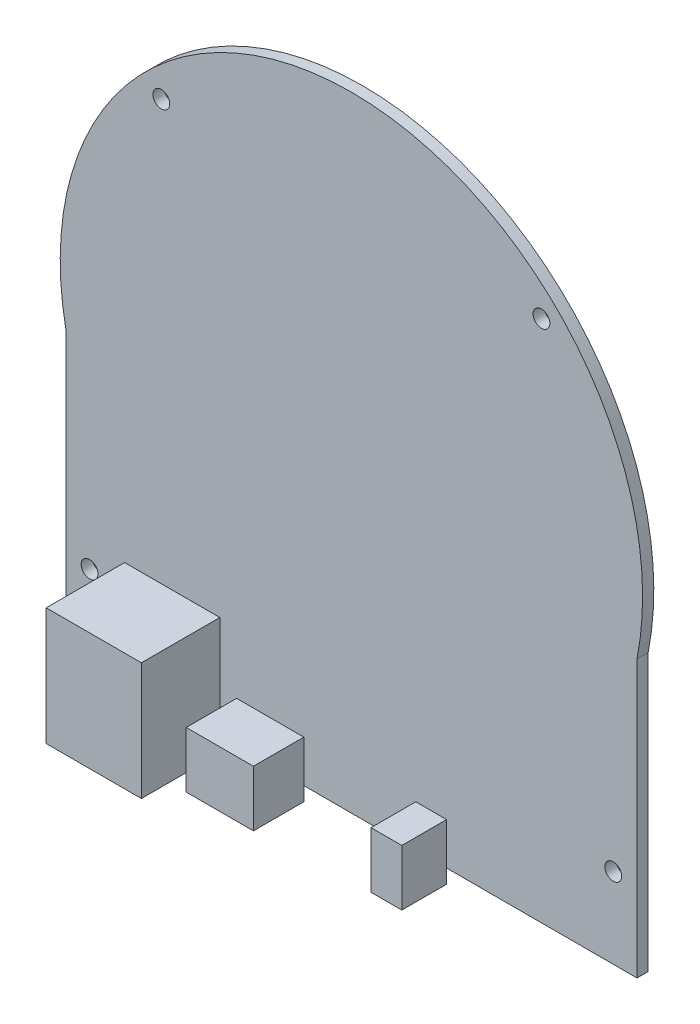
SolidWorks part; units mm, degrees
ref_plane "Plan de face" through (0, 0, 0) normal (0, 0, 1) x (1, 0, 0)
ref_plane "Plan de dessus" through (0, 0, 0) normal (0, 1, 0) x (1, 0, 0)
ref_plane "Plan de droite" through (0, 0, 0) normal (1, 0, 0) x (0, 0, -1)
sketch "Esquisse1" plane through (0, 0, 0) normal (0, 0, 1) x (1, 0, 0)
  line L0 (-51, -59.5) -> (51, -59.5)
  line L1 (-51, -59.5) -> (-51, -10.1489)
  line L2 (51, -59.5) -> (51, -10.1489)
  line L3 (0, 0) -> (-92.6782, 92.6782) construction
  line L4 (0, 0) -> (-109.0276, -105.2868) construction
  line L5 (0, 0) -> (0, 109.9392) construction
  arc A0 (51, -10.1489) -> (-51, -10.1489) centre (0, 0) ccw
  circle A1 centre (0, 0) radius 48 construction
  circle A2 centre (0, 0) radius 65 construction
  circle A3 centre (-33.9411, 33.9411) radius 1.5
  circle A4 centre (-46.7571, -45.1528) radius 1.5
  circle A5 centre (33.9411, 33.9411) radius 1.5
  circle A6 centre (46.7571, -45.1528) radius 1.5
  dimension "D1" = 104
  dimension "D5" = 96
  dimension "D6" = 130
  dimension "D9" = 3
  dimension "D10" = 3
  dimension "D2" = 59.5
  dimension "D3" = 51
  dimension "D4" = 102
  dimension "D7" = 45
  dimension "D8" = 46
extrude "Boss.-Extru.1" add sketch "Esquisse1" along normal blind 2
ref_plane "Plan1" through (0, -61.5, 0) normal (0, -1, 0) x (1, 0, 0)
sketch "Esquisse2" plane through (0, -61.5, 0) normal (0, -1, 0) x (1, 0, 0)
  line L0 (-31.5, 16.5) -> (-31.5, 2.5) construction
  line L1 (-40, 16.5) -> (-23, 16.5)
  line L2 (-40, 16.5) -> (-40, 2.5)
  line L3 (-40, 2.5) -> (-23, 2.5)
  line L4 (-23, 16.5) -> (-23, 2.5)
  line L5 (-29.5, 3.5) -> (-33.5, 3.5)
  line L6 (-33.5, 3.5) -> (-33.5, 4.5)
  line L7 (-33.5, 4.5) -> (-34.5, 4.5)
  line L8 (-34.5, 4.5) -> (-34.5, 6)
  line L9 (-34.5, 6) -> (-39, 6)
  line L10 (-39, 6) -> (-39, 14.5)
  line L11 (-39, 14.5) -> (-24, 14.5)
  line L12 (-29.5, 3.5) -> (-29.5, 4.5)
  line L13 (-29.5, 4.5) -> (-28.5, 4.5)
  line L14 (-28.5, 4.5) -> (-28.5, 6)
  line L15 (-28.5, 6) -> (-24, 6)
  line L16 (-24, 6) -> (-24, 14.5)
  point P16 (-31.5, 3.5)
  point P21 (-31.5, 14.5)
  dimension "D1" = 17
  dimension "D2" = 14
  dimension "D3" = 2.5
  dimension "D4" = 40
  dimension "D5" = 2
  dimension "D6" = 1
  dimension "D7" = 1
  dimension "D8" = 1.5
  dimension "D9" = 2
  dimension "D10" = 1
  dimension "D11" = 1
extrude "Boss.-Extru.2" add sketch "Esquisse2" against normal blind 21 separate body contours L2 L3 L4 L1
sketch "Esquisse3" plane through (0, -61.5, 0) normal (0, -1, 0) x (1, 0, 0)
  line L11 (-39, 14.5) -> (-24, 14.5) construction
  line L12 (-39, 6) -> (-39, 14.5) construction
  line L13 (-34.5, 6) -> (-39, 6) construction
  line L14 (-34.5, 4.5) -> (-34.5, 6) construction
  line L15 (-33.5, 4.5) -> (-34.5, 4.5) construction
  line L16 (-33.5, 3.5) -> (-33.5, 4.5) construction
  line L17 (-29.5, 3.5) -> (-33.5, 3.5) construction
  line L18 (-29.5, 3.5) -> (-29.5, 4.5) construction
  line L19 (-29.5, 4.5) -> (-28.5, 4.5) construction
  line L20 (-28.5, 4.5) -> (-28.5, 6) construction
  line L21 (-28.5, 6) -> (-24, 6) construction
  line L22 (-24, 6) -> (-24, 14.5) construction
  line L23 (-39, 14.5) -> (-24, 14.5)
  line L24 (-39, 6) -> (-39, 14.5)
  line L25 (-34.5, 6) -> (-39, 6)
  line L26 (-34.5, 4.5) -> (-34.5, 6)
  line L27 (-33.5, 4.5) -> (-34.5, 4.5)
  line L28 (-33.5, 3.5) -> (-33.5, 4.5)
  line L29 (-29.5, 3.5) -> (-33.5, 3.5)
  line L30 (-29.5, 3.5) -> (-29.5, 4.5)
  line L31 (-29.5, 4.5) -> (-28.5, 4.5)
  line L32 (-28.5, 4.5) -> (-28.5, 6)
  line L33 (-28.5, 6) -> (-24, 6)
  line L34 (-24, 6) -> (-24, 14.5)
extrude "Enlèv. mat.-Extru.1" cut sketch "Esquisse3" against normal blind 15
sketch "Esquisse4" plane through (0, -61.5, 0) normal (0, -1, 0) x (1, 0, 0)
  line L0 (-23, 16.5) -> (-23, 2.5) construction
  line L1 (-20, 2.5) -> (-8, 2.5)
  line L2 (-20, 2.5) -> (-20, 11.5)
  line L3 (-20, 11.5) -> (-8, 11.5)
  line L4 (-8, 2.5) -> (-8, 11.5)
  dimension "D1" = 3
  dimension "D2" = 12
  dimension "D3" = 9
  dimension "D4" = 2.5
extrude "Boss.-Extru.3" add sketch "Esquisse4" against normal blind 10 separate body
sketch "Esquisse5" plane through (0, -61.5, 0) normal (0, -1, 0) x (1, 0, 0)
  line L0 (-19.5, 3) -> (-8.5, 3)
  line L1 (-8.5, 3) -> (-8.5, 10)
  line L2 (-8.5, 10) -> (-9, 10)
  line L3 (-9, 10) -> (-9, 10.25)
  line L4 (-9, 10.25) -> (-8.5, 10.25)
  line L5 (-8.5, 10.25) -> (-8.5, 11)
  line L6 (-8.5, 11) -> (-10.5, 11)
  line L7 (-10.5, 11) -> (-10.5, 10.25)
  line L8 (-10.5, 10.25) -> (-10, 10.25)
  line L9 (-10, 10.25) -> (-10, 10)
  line L10 (-10, 10) -> (-10.75, 10)
  line L11 (-8, 2.5) -> (-8, 11.5) construction
  line L12 (-20, 2.5) -> (-8, 2.5) construction
  line L13 (-12.25, 10) -> (-13, 10)
  line L14 (-12.25, 10.25) -> (-12.25, 10)
  line L15 (-12.75, 10.25) -> (-12.25, 10.25)
  line L16 (-12.75, 11) -> (-12.75, 10.25)
  line L17 (-10.75, 11) -> (-12.75, 11)
  line L18 (-10.75, 10.25) -> (-10.75, 11)
  line L19 (-11.25, 10.25) -> (-10.75, 10.25)
  line L20 (-11.25, 10) -> (-11.25, 10.25)
  line L21 (-10.75, 10) -> (-11.25, 10)
  line L22 (-14.5, 10) -> (-15.25, 10)
  line L23 (-14.5, 10.25) -> (-14.5, 10)
  line L24 (-15, 10.25) -> (-14.5, 10.25)
  line L25 (-15, 11) -> (-15, 10.25)
  line L26 (-13, 11) -> (-15, 11)
  line L27 (-13, 10.25) -> (-13, 11)
  line L28 (-13.5, 10.25) -> (-13, 10.25)
  line L29 (-13.5, 10) -> (-13.5, 10.25)
  line L30 (-13, 10) -> (-13.5, 10)
  line L31 (-16.75, 10) -> (-17.5, 10)
  line L32 (-16.75, 10.25) -> (-16.75, 10)
  line L33 (-17.25, 10.25) -> (-16.75, 10.25)
  line L34 (-17.25, 11) -> (-17.25, 10.25)
  line L35 (-15.25, 11) -> (-17.25, 11)
  line L36 (-15.25, 10.25) -> (-15.25, 11)
  line L37 (-15.75, 10.25) -> (-15.25, 10.25)
  line L38 (-15.75, 10) -> (-15.75, 10.25)
  line L39 (-15.25, 10) -> (-15.75, 10)
  line L40 (-19, 10) -> (-19.5, 10)
  line L41 (-19, 10.25) -> (-19, 10)
  line L42 (-19.5, 10.25) -> (-19, 10.25)
  line L43 (-19.5, 11) -> (-19.5, 10.25)
  line L44 (-17.5, 11) -> (-19.5, 11)
  line L45 (-17.5, 10.25) -> (-17.5, 11)
  line L46 (-18, 10.25) -> (-17.5, 10.25)
  line L47 (-18, 10) -> (-18, 10.25)
  line L48 (-17.5, 10) -> (-18, 10)
  line L50 (-19.5, 10) -> (-19.5, 3)
  dimension "D1" = 2
  dimension "D2" = 0.5
  dimension "D3" = 0.5
  dimension "D4" = 0.75
  dimension "D5" = 0.75
  dimension "D6" = 0.5
  dimension "D7" = 0.5
  dimension "D8" = 0.25
  dimension "D9" = 7
  dimension "D10" = 0.75
  dimension "D11" = 5
extrude "Enlèv. mat.-Extru.2" cut sketch "Esquisse5" against normal blind 8
sketch "Esquisse6" plane through (0, -53.5, 0) normal (0, -1, 0) x (1, 0, 0)
  circle A0 centre (-18.5478, 6.6182) radius 0.375
  circle A1 centre (-16.2978, 6.6182) radius 0.375
  circle A2 centre (-14.0478, 6.6182) radius 0.375
  circle A3 centre (-11.7978, 6.6182) radius 0.375
  circle A4 centre (-9.5478, 6.6182) radius 0.375
  dimension "D1" = 0.75
  dimension "D2" = 5
extrude "Boss.-Extru.4" add sketch "Esquisse6" along normal blind 6
sketch "Esquisse7" plane through (0, -61.5, 0) normal (0, -1, 0) x (1, 0, 0)
  line L1 (12, 2.5) -> (17.5, 2.5)
  line L2 (12, 2.5) -> (12, 10.5)
  line L3 (12, 10.5) -> (17.5, 10.5)
  line L4 (17.5, 2.5) -> (17.5, 10.5)
  dimension "D1" = 5.5
  dimension "D2" = 8
  dimension "D3" = 2.5
  dimension "D4" = 20
extrude "Boss.-Extru.5" add sketch "Esquisse7" against normal blind 10 separate body
sketch "Esquisse8" plane through (0, -61.5, 0) normal (0, -1, 0) x (1, 0, 0)
  line L0 (14.75, 10.5) -> (14.75, -2.8248) construction
  line L1 (17.5, 10.5) -> (12, 10.5) construction
  circle A0 centre (14.75, 6.9772) radius 2
  dimension "D1" = 4
extrude "Enlèv. mat.-Extru.3" cut sketch "Esquisse8" against normal blind 8
sketch "Esquisse9" plane through (0, -53.5, 0) normal (0, -1, 0) x (1, 0, 0)
  circle A0 centre (14.75, 6.9772) radius 0.5
  dimension "D1" = 1
extrude "Boss.-Extru.6" add sketch "Esquisse9" along normal blind 8
sketch "Esquisse10" plane through (0, 0, 2) normal (0, 0, 1) x (1, 0, 0)
  line L1 (0, 0) -> (-24, 0)
  line L2 (0, 0) -> (0, 24)
  line L3 (0, 24) -> (-24, 24)
  line L4 (-24, 0) -> (-24, 24)
  line L5 (12, 17) -> (24, 17)
  line L6 (12, 17) -> (12, -7)
  line L7 (12, -7) -> (24, -7)
  line L8 (24, 17) -> (24, -7)
  line L9 (30, 17) -> (42, 17)
  line L10 (30, 17) -> (30, -7)
  line L11 (30, -7) -> (42, -7)
  line L12 (42, 17) -> (42, -7)
  line L13 (-30, -30) -> (-15, -30)
  line L14 (-30, -30) -> (-30, -10)
  line L15 (-30, -10) -> (-15, -10)
  line L16 (-15, -30) -> (-15, -10)
  dimension "D1" = 24
  dimension "D2" = 24
  dimension "D3" = 24
  dimension "D4" = 24
  dimension "D5" = 12
  dimension "D6" = 12
  dimension "D7" = 17
  dimension "D8" = 12
  dimension "D9" = 6
  dimension "D10" = 15
  dimension "D11" = 20
  dimension "D12" = 10
  dimension "D13" = 15
extrude "Boss.-Extru.7" [suppressed] add sketch "Esquisse10" along normal blind 3
sketch "Esquisse11" plane through (0, 0, 2) normal (0, 0, 1) x (1, 0, 0)
  circle A0 centre (23.8359, -44.6172) radius 2.8691
  circle A1 centre (15.8203, -39.5547) radius 3.1641
  circle A2 centre (8.2266, -39.5547) radius 2.4051
  circle A3 centre (14.1328, -32.1719) radius 2.54
  circle A4 centre (5.8215, -32.1719) radius 3.3929
  circle A5 centre (5.8215, -22.0469) radius 2.8221
  circle A6 centre (14.1328, -19.2247) radius 3.5262
  circle A7 centre (-1.2656, -35.5647) radius 1.7773
extrude "Boss.-Extru.8" [suppressed] add sketch "Esquisse11" along normal blind 8
ref_plane "Plan2" [suppressed] through (-23.75, 0, 0) normal (-1, 0, 0) x (0, 0, 1)
sketch "Esquisse12" [suppressed] plane through (-23.75, 0, 0) normal (-1, 0, 0) x (0, 0, 1)
  line L0 (3.5, 0) -> (3.5, -1) construction
  line L1 (5, 0) -> (2, 0) construction
  line L2 (3.5, -1) -> (2, -1) construction
  line L3 (2, 17) -> (2, -7) construction
  spline S0 degree 3 poles (3.5, 0) (3.5, -0.25) (3.5, -0.5) (3.5, -0.75) (3.5, -0.8001) (3.5, -0.9002) (3.2752, -1) (3.1751, -1) (3.125, -1) (2.75, -1) (2.375, -1) (2, -1) knots 0 0 0 0 0.322484 0.322484 0.322484 0.387081 0.451677 0.516273 0.516273 0.516273 1 1 1 1
  dimension "D1" = 1
sketch "Esquisse13" [suppressed] plane through (0, 0, 0) normal (0, -1, 0) x (1, 0, 0)
  circle A0 centre (-23.75, 3.5) radius 0.15
  dimension "D1" = 0.3
sweep "Balayage1" [suppressed] add profiles "Esquisse13" path "Esquisse12"
pattern_linear "Répétition linéaire2" [suppressed] count 48 spacing 0.5
ref_plane "Plan3" [suppressed] through (-12, 12, 0) normal (0.7071, -0.7071, 0) x (0, 0, -1)
mirror "Symétrie1" [suppressed] about plane through (-12, 12, 0) normal (0.7071, -0.7071, 0)
